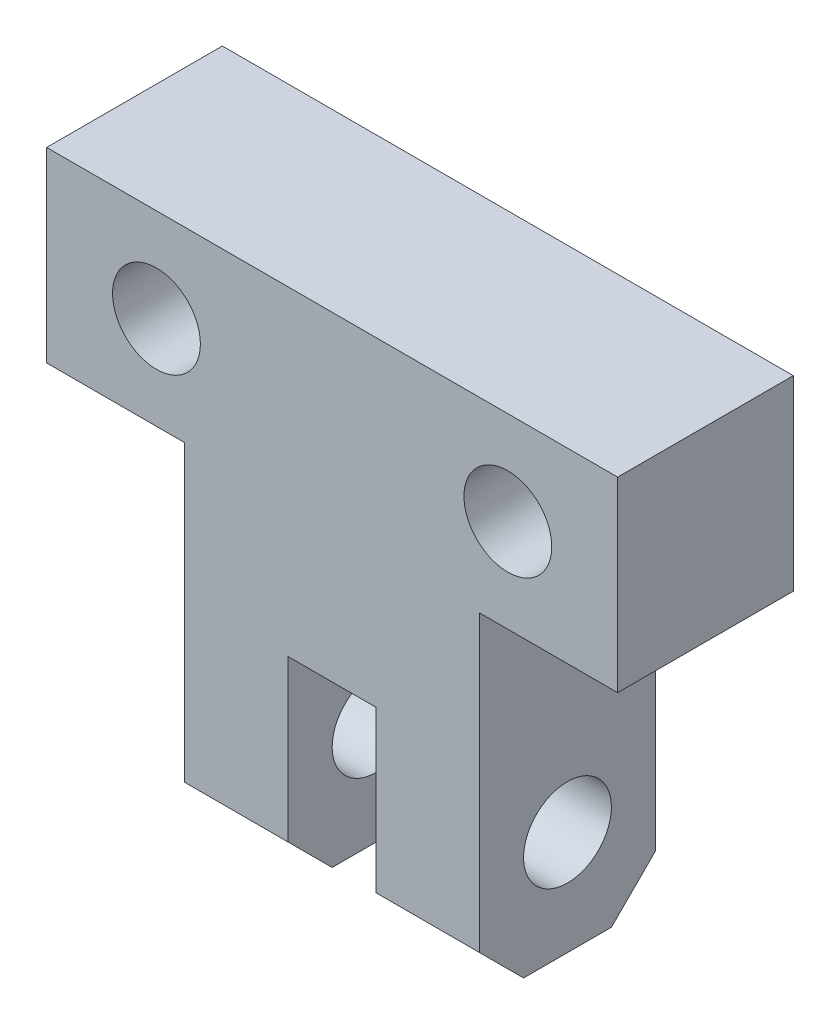
SolidWorks part; units mm, degrees
ref_plane "Спереди" through (0, 0, 0) normal (0, 0, 1) x (1, 0, 0)
ref_plane "Сверху" through (0, 0, 0) normal (0, 1, 0) x (1, 0, 0)
ref_plane "Справа" through (0, 0, 0) normal (1, 0, 0) x (0, 0, -1)
sketch "Эскиз1" plane through (0, 0, 0) normal (0, 0, 1) x (1, 0, 0)
  line L0 (0, -20) -> (0, 20.9509) construction
  line L1 (-13, 15) -> (13, 15)
  line L2 (-13, 15) -> (-13, 6.5)
  line L3 (6.7163, -8.8945) -> (2, -8.8945)
  line L4 (6.7163, 6.5) -> (13, 6.5)
  line L5 (-2, -8.8945) -> (-2, 0.4213)
  line L6 (-6.7163, 6.5) -> (-13, 6.5)
  line L7 (6.7163, -8.8945) -> (6.7163, 6.5)
  line L8 (13, 15) -> (13, 6.5)
  line L10 (2, -8.8945) -> (2, 0.4213)
  line L11 (2, 0.4213) -> (-2, 0.4213)
  line L12 (-6.7163, -8.8945) -> (-2, -8.8945)
  line L13 (-6.7163, -8.8945) -> (-6.7163, 6.5)
  point P9 (0, 0.4213)
  dimension "D1" = 13
extrude "Вытянуть1" add sketch "Эскиз1" along normal blind 8
sketch "Эскиз2" plane through (0, 0, 8) normal (0, 0, 1) x (1, 0, 0)
  line L0 (-13, 15) -> (-13, 6.5) construction
  line L2 (-11, 10.75) -> (2.3249, 10.75) construction
  line L4 (13, 6.5) -> (13, 15) construction
  circle A0 centre (-8, 10.7485) radius 2
  circle A1 centre (8, 10.75) radius 2
  dimension "D1" = 5
  dimension "D2" = 5
extrude "Вытянуть2" cut sketch "Эскиз2" against normal through all
sketch "Эскиз3" plane through (6.7163, 0, 0) normal (1, 0, 0) x (0, 0, -1)
  circle A0 centre (-4, -4.1483) radius 2
extrude "Вырез-Вытянуть1" cut sketch "Эскиз3" against normal through all
chamfer "Фаска1" distance 2 angle 45 4 edges at (-4.3581, -8.8945, 8) (4.3581, -8.8945, 8) (-4.3581, -8.8945, 0) (4.3581, -8.8945, 0)
